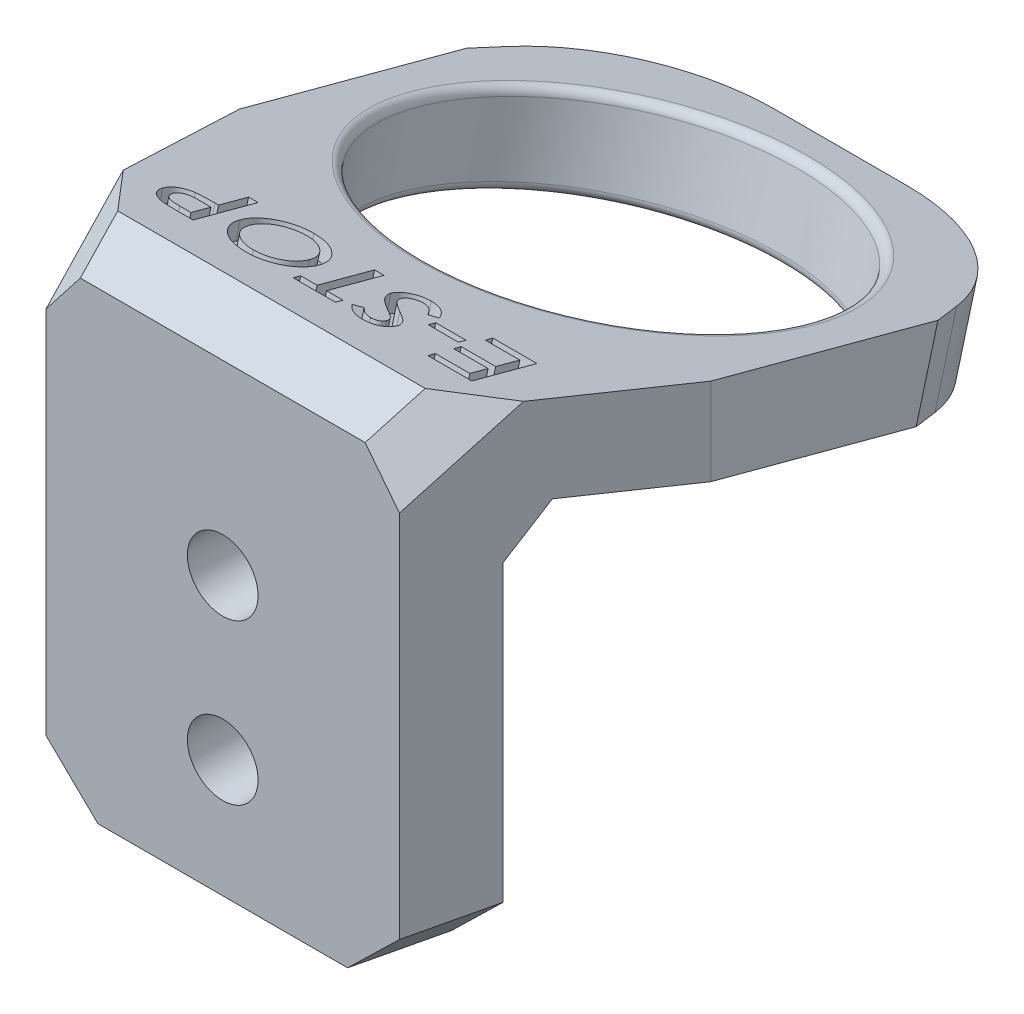
SolidWorks part; units mm, degrees
ref_plane "Front Plane" through (0, 0, 0) normal (0, 0, 1) x (1, 0, 0)
ref_plane "Top Plane" through (0, 0, 0) normal (0, 1, 0) x (1, 0, 0)
ref_plane "Right Plane" through (0, 0, 0) normal (1, 0, 0) x (0, 0, -1)
sketch "Sketch1" plane through (0, 0, 0) normal (1, 0, 0) x (0, 0, -1)
  line L0 (0, 0) -> (0, -30)
  line L1 (0, -30) -> (5, -30)
  line L2 (5, -30) -> (5, -6.5161)
  line L3 (5, -6.5161) -> (35.4111, -14.6648)
  line L4 (35.4111, -14.6648) -> (36.7052, -9.8351)
  line L5 (36.7052, -9.8351) -> (0, 0)
  dimension "D1" = 30
  dimension "D2" = 5
  dimension "D3" = 75
  dimension "D4" = 5
  dimension "D5" = 38
extrude "Boss-Extrude1" add sketch "Sketch1" along normal blind 28
sketch "Sketch2" plane through (0, 0, 0) normal (0, 1, 0) x (1, 0, 0)
  line L0 (3.5, 0) -> (0, 15)
  line L1 (28, 0) -> (0, 0) construction
  line L2 (0, 36.7052) -> (0, 0) construction
  line L3 (0, 15) -> (0, 0)
  line L4 (0, 0) -> (3.5, 0)
  line L5 (14, 0) -> (14, 36.7052) construction
  line L6 (28, 36.7052) -> (0, 36.7052) construction
  line L7 (28, 0) -> (24.5, 0)
  line L8 (28, 15) -> (28, 0)
  line L9 (24.5, 0) -> (28, 15)
  dimension "D1" = 3.5
  dimension "D2" = 15
extrude "Cut-Extrude1" cut sketch "Sketch2" against normal blind 50
sketch "Sketch3" plane through (0, 0, 0) normal (0, 0.9659, -0.2588) x (1, 0, 0)
  line L0 (14, 38) -> (14, 0) construction
  line L1 (28, 38) -> (0, 38) construction
  line L2 (24.5, 0) -> (3.5, 0) construction
  line L3 (3, 38) -> (0, 29.5)
  line L4 (0, 38) -> (0, 15.5291) construction
  line L5 (0, 29.5) -> (0, 38)
  line L6 (0, 38) -> (3, 38)
  line L7 (28, 38) -> (25, 38)
  line L8 (28, 29.5) -> (28, 38)
  line L9 (25, 38) -> (28, 29.5)
  circle A0 centre (14, 24) radius 11.5
  dimension "D2" = 23
  dimension "D1" = 14
  dimension "D3" = 3
  dimension "D4" = 8.5
extrude "Cut-Extrude2" cut sketch "Sketch3" against normal up to surface (5 mm away) up to face at (14, -10.1255, -18.4704)
chamfer "Chamfer1" distance 3 angle 45 2 edges at (25.0833, -30, -2.5) (2.9167, -30, -2.5)
sketch "Sketch4" plane through (0, 0, -5) normal (0, 0, -1) x (-1, 0, 0)
  line L0 (-14, -30) -> (-14, -6.5161) construction
  line L1 (-22.5861, -30) -> (-5.4139, -30) construction
  line L2 (-25.6667, -6.5161) -> (-2.3333, -6.5161) construction
  circle A0 centre (-14, -13.5161) radius 2.1
  circle A1 centre (-14, -23) radius 2.1
  dimension "D3" = 4.2
  dimension "D1" = 7
  dimension "D2" = 7
extrude "Cut-Extrude3" cut sketch "Sketch4" against normal up to surface (5 mm away) up to face at (14, -19, 0)
chamfer "Chamfer2" distance 3 angle 45 2 edges at (14, 0, 0) (14, -6.5161, -5)
fillet "Fillet1" radius 0.5 2 edges at (14, -8.0649, -10.78) (14, -3.2352, -12.0741)
chamfer "Chamfer3" distance 1 angle 45 2 edges at (11.9, -23, -5) (11.9, -13.5161, -5)
fillet "Fillet2" radius 10 2 edges at (3, -12.2499, -36.0581) (25, -12.2499, -36.0581)
chamfer "Chamfer4" distance 2 angle 45 2 edges at (24.8381, -1.613, -1.4489) (3.1619, -1.613, -1.4489)
sketch "Sketch5" plane through (0, 0, 0) normal (0, 0.9659, -0.2588) x (1, 0, 0)
  line L0 (24, 9.5) -> (4, 9.5) construction
  line L1 (14, 3) -> (14, 9.5) construction
  line L2 (4.8643, 3) -> (23.1357, 3) construction
  text T0 "E-STOP" font "Century Gothic" height 4
  dimension "D1" = 6.5
  dimension "D2" = 20
extrude "Cut-Extrude4" cut sketch "Sketch5" against normal blind 1
